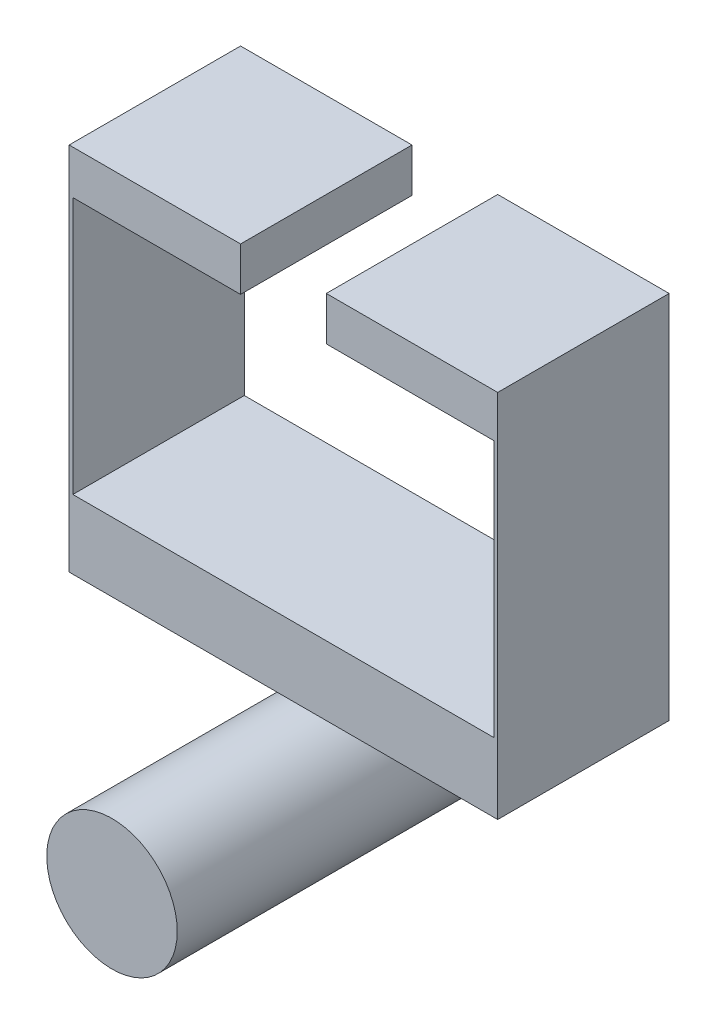
SolidWorks part; units mm, degrees
material "Titanium"
ref_plane "Front Plane" through (0, 0, 0) normal (0, 0, 1) x (1, 0, 0)
ref_plane "Top Plane" through (0, 0, 0) normal (0, 1, 0) x (1, 0, 0)
ref_plane "Right Plane" through (0, 0, 0) normal (1, 0, 0) x (0, 0, -1)
sketch "Sketch1" plane through (0, 0, 0) normal (0, 0, 1) x (1, 0, 0)
  circle A0 centre (0, 0) radius 9.6672
  dimension "D1" = 19.3344
extrude "Boss-Extrude1" add sketch "Sketch1" along normal blind 50.8
sketch "Sketch2" plane through (0, 0, 0) normal (0, 0, -1) x (-1, 0, 0)
  line L0 (9.6672, 0) -> (9.6672, 12.7)
  line L1 (9.6672, 12.7) -> (-9.6672, 12.7)
  line L2 (-9.6672, 12.7) -> (-9.6672, 0)
  line L3 (-9.6672, 0) -> (9.6672, 0)
  circle A1 centre (0, 0) radius 9.6672 construction
  dimension "D1" = 12.7
extrude "Boss-Extrude2" add sketch "Sketch2" against normal blind 8.89
sketch "Sketch4" plane through (0, 0, 0) normal (0, 0, -1) x (-1, 0, 0)
  line L0 (-31.75, 12.7) -> (-31.75, 22.9352)
  line L2 (-31.75, 22.9352) -> (31.75, 22.9352)
  line L3 (31.75, 22.9352) -> (31.75, 12.7)
  line L4 (-31.75, 12.7) -> (-9.6672, 12.7)
  line L5 (9.6672, 12.7) -> (31.75, 12.7)
  line L6 (-9.6672, 12.7) -> (9.6672, 12.7)
  dimension "D1" = 63.5
  dimension "D2" = 10.2352
extrude "Boss-Extrude3" add sketch "Sketch4" against normal blind 25.4
sketch "Sketch5" plane through (0, 0, 0) normal (0, 0, -1) x (-1, 0, 0)
  line L0 (0, 0) -> (0, 44.2128) construction
  line L2 (31.75, 22.9352) -> (31.2001, 22.9352)
  line L3 (31.75, 22.9352) -> (31.75, 61.0352)
  line L4 (31.75, 61.0352) -> (31.2001, 61.0352)
  line L5 (31.2001, 22.9352) -> (31.2001, 61.0352)
  line L6 (-31.75, 22.9352) -> (-31.2001, 22.9352)
  line L7 (-31.75, 22.9352) -> (-31.75, 61.0352)
  line L8 (-31.75, 61.0352) -> (-31.2001, 61.0352)
  line L9 (-31.2001, 22.9352) -> (-31.2001, 61.0352)
  dimension "D1" = 38.1
  dimension "D2" = 0.5499
extrude "Boss-Extrude4" add sketch "Sketch5" against normal blind 25.4
sketch "Sketch6" plane through (0, 0, 0) normal (0, 0, -1) x (-1, 0, 0)
  line L1 (31.75, 61.0352) -> (6.35, 61.0352)
  line L2 (31.75, 61.0352) -> (31.75, 67.5085)
  line L3 (31.75, 67.5085) -> (6.35, 67.5085)
  line L4 (6.35, 61.0352) -> (6.35, 67.5085)
  line L5 (-31.75, 61.0352) -> (-6.35, 61.0352)
  line L6 (-31.75, 61.0352) -> (-31.75, 67.5085)
  line L7 (-31.75, 67.5085) -> (-6.35, 67.5085)
  line L8 (-6.35, 61.0352) -> (-6.35, 67.5085)
  dimension "D1" = 6.4733
  dimension "D2" = 25.4
extrude "Boss-Extrude5" add sketch "Sketch6" against normal blind 25.4
equation "\"SF\"= 4"
equation "\"W\"= 1300"
equation "\"F\"= 650"
equation "\"L1\"= 2in"
equation "\"SY\"= 120091"
equation "\"E\"= 16534300"
equation "\"z\"= ( \"SF\" * \"W\" * \"L1\" ) / ( 2 * \"SY\" )"
equation "\"r1\"= ( 4 * ( \"z\" / pi ) ) ^ ( 1 / 3 )"
equation "\"d1\"= 2 * \"r1\""
equation "\"L2\"= .5in"
equation "\"T2\"= ( \"W\" * \"SF\" ) / ( \"d1\" * \"SY\" )"
equation "\"L3\"= 2.5in"
equation "\"b3\"= 1in"
equation "\"T3\"= ( ( 1.5 * \"L3\" * \"W\" * \"SF\" ) / ( \"b3\" * \"SY\" ) ) ^ ( 1 / 2 )"
equation "\"T4\"= 1.5in"
equation "\"W4\"= 1in"
equation "\"L4\"= ( \"F\" * \"SF\" ) / ( \"W4\" * \"SY\" )"
equation "\"W5\"= 1in"
equation "\"L5\"= 1in"
equation "\"T5\"= ( ( 1.5 * \"W\" * \"L5\" * \"SF\" ) / ( \"W5\" * \"SY\" ) ) ^ ( 1 / 2 )"
equation "\"D1@Sketch1\"= \"d1\""
equation "\"D1@Boss-Extrude1\"=\"L1\""
equation "\"D1@Sketch2\"=\"L2\""
equation "\"D1@Boss-Extrude2\"=.35"
equation "\"D1@Sketch4\"= \"L3\""
equation "\"D2@Sketch4\"= \"T3\""
equation "\"W3\"= 1in"
equation "\"D1@Boss-Extrude3\"=\"W3\""
equation "\"D1@Sketch5\"= \"T4\""
equation "\"D2@Sketch5\"= \"L4\""
equation "\"D1@Boss-Extrude4\"=\"W4\""
equation "\"D1@Sketch6\"= \"T5\""
equation "\"D2@Sketch6\"= \"L5\""
equation "\"D1@Boss-Extrude5\"= \"W5\""
